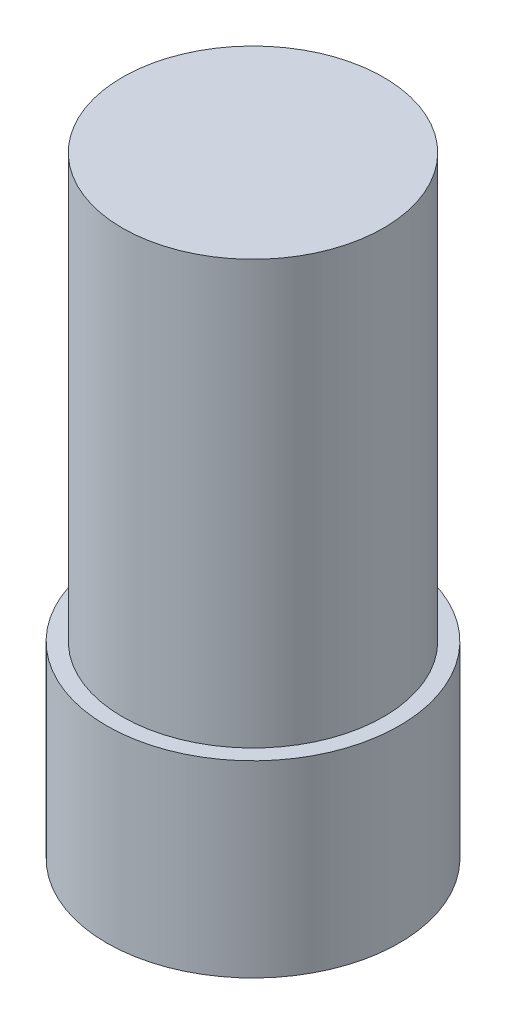
SolidWorks part; units mm, degrees
ref_plane "前视基准面" through (0, 0, 0) normal (0, 0, 1) x (1, 0, 0)
ref_plane "上视基准面" through (0, 0, 0) normal (0, 1, 0) x (1, 0, 0)
ref_plane "右视基准面" through (0, 0, 0) normal (1, 0, 0) x (0, 0, -1)
sketch "草图1" plane through (0, 0, 0) normal (0, 1, 0) x (1, 0, 0)
  circle A0 centre (0, 0) radius 14
  dimension "D1" = 28
extrude "凸台-拉伸1" add sketch "草图1" along normal blind 18
sketch "草图2" plane through (0, 18, 0) normal (0, 1, 0) x (1, 0, 0)
  circle A0 centre (0, 0) radius 12.5
  dimension "D1" = 25
extrude "凸台-拉伸2" add sketch "草图2" along normal blind 40.5
